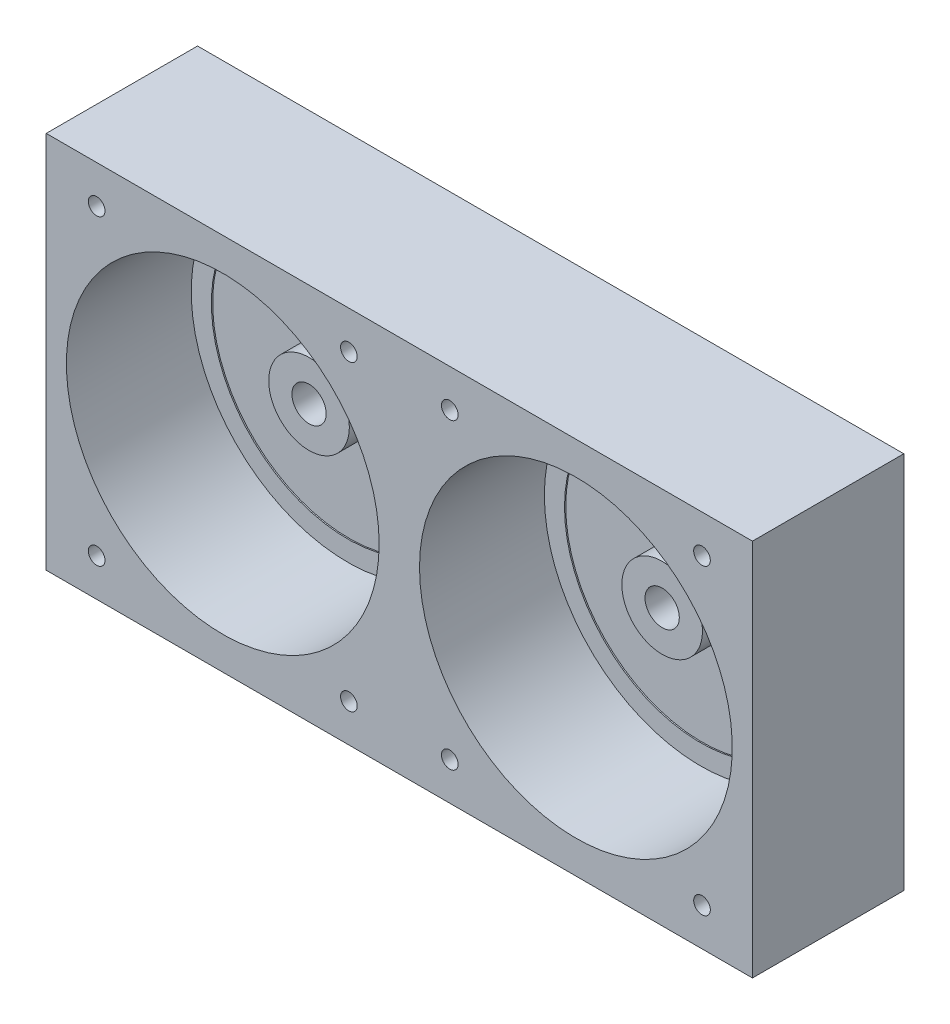
SolidWorks part; units mm, degrees
other "Objet de détail2"
other "Objet de détail3"
ref_plane "Plan de face" through (0, 0, 0) normal (0, 0, 1) x (1, 0, 0)
ref_plane "Plan de dessus" through (0, 0, 0) normal (0, 1, 0) x (1, 0, 0)
ref_plane "Plan de droite" through (0, 0, 0) normal (1, 0, 0) x (0, 0, -1)
sketch "Esquisse1" plane through (0, 0, 0) normal (0, 0, 1) x (1, 0, 0)
  line L1 (0, 0) -> (140, 0)
  line L2 (0, 0) -> (0, 75)
  line L3 (0, 75) -> (140, 75)
  line L4 (140, 0) -> (140, 75)
  dimension "D1" = 75
  dimension "D2" = 140
extrude "Boss.-Extru.1" add sketch "Esquisse1" along normal blind 30
sketch "Esquisse2" plane through (0, 0, 30) normal (0, 0, 1) x (1, 0, 0)
  line L0 (70, 0) -> (70, 75) construction
  line L1 (0, 0) -> (140, 0) construction
  line L2 (140, 75) -> (0, 75) construction
  line L3 (35, 37.5) -> (70, 37.5) construction
  circle A0 centre (35, 37.5) radius 31
  circle A1 centre (105, 37.5) radius 31
  dimension "D1" = 62
  dimension "D2" = 35
extrude "Enlèv. mat.-Extru.1" cut sketch "Esquisse2" against normal blind 25
sketch "Esquisse3" plane through (0, 0, 5) normal (0, 0, 1) x (1, 0, 0)
  line L0 (70, 0) -> (70, 75) construction
  line L1 (0, 0) -> (140, 0) construction
  line L2 (140, 75) -> (0, 75) construction
  circle A0 centre (35, 37.5) radius 3.4
  circle A1 centre (35, 37.5) radius 31 construction
  circle A2 centre (105, 37.5) radius 3.4
  dimension "D1" = 6.8
extrude "Enlèv. mat.-Extru.2" cut sketch "Esquisse3" against normal through all both and the other way through all
sketch "Esquisse4" plane through (0, 0, 5) normal (0, 0, 1) x (1, 0, 0)
  line L0 (70, 0) -> (70, 75) construction
  line L1 (0, 0) -> (140, 0) construction
  line L2 (140, 75) -> (0, 75) construction
  circle A0 centre (35, 37.5) radius 31
  circle A1 centre (35, 37.5) radius 27.01
  circle A2 centre (105, 37.5) radius 27.01
  circle A3 centre (105, 37.5) radius 31
  dimension "D1" = 54.02
  dimension "D2" = 62
extrude "Boss.-Extru.2" add sketch "Esquisse4" along normal blind 0.25
sketch "Esquisse5" plane through (0, 0, 5) normal (0, 0, 1) x (1, 0, 0)
  circle A0 centre (35, 37.5) radius 7.99
  circle A1 centre (105, 37.5) radius 7.99
  circle A2 centre (35, 37.5) radius 3.4
  circle A3 centre (105, 37.5) radius 3.4
  circle A4 centre (35, 37.5) radius 3.4 construction
  dimension "D1" = 15.98
extrude "Boss.-Extru.3" add sketch "Esquisse5" along normal blind 7.9
sketch "Esquisse6" plane through (0, 0, 30) normal (0, 0, 1) x (1, 0, 0)
  line L0 (70, 0) -> (70, 75) construction
  line L1 (0, 0) -> (140, 0) construction
  line L2 (140, 75) -> (0, 75) construction
  line L3 (0, 37.5) -> (70, 37.5) construction
  line L4 (0, 75) -> (0, 0) construction
  line L5 (60, 67.5) -> (10, 67.5) construction
  line L6 (60, 7.5) -> (10, 7.5) construction
  line L7 (80, 7.5) -> (130, 7.5) construction
  line L8 (80, 67.5) -> (130, 67.5) construction
  circle A0 centre (60, 67.5) radius 1.65
  circle A1 centre (10, 67.5) radius 1.65
  circle A2 centre (10, 7.5) radius 1.65
  circle A3 centre (60, 7.5) radius 1.65
  circle A4 centre (80, 7.5) radius 1.65
  circle A5 centre (130, 7.5) radius 1.65
  circle A6 centre (130, 67.5) radius 1.65
  circle A7 centre (80, 67.5) radius 1.65
  dimension "D1" = 3.3
  dimension "D4" = 60
  dimension "D2" = 10
  dimension "D3" = 30
extrude "Enlèv. mat.-Extru.3" cut sketch "Esquisse6" against normal blind 20
